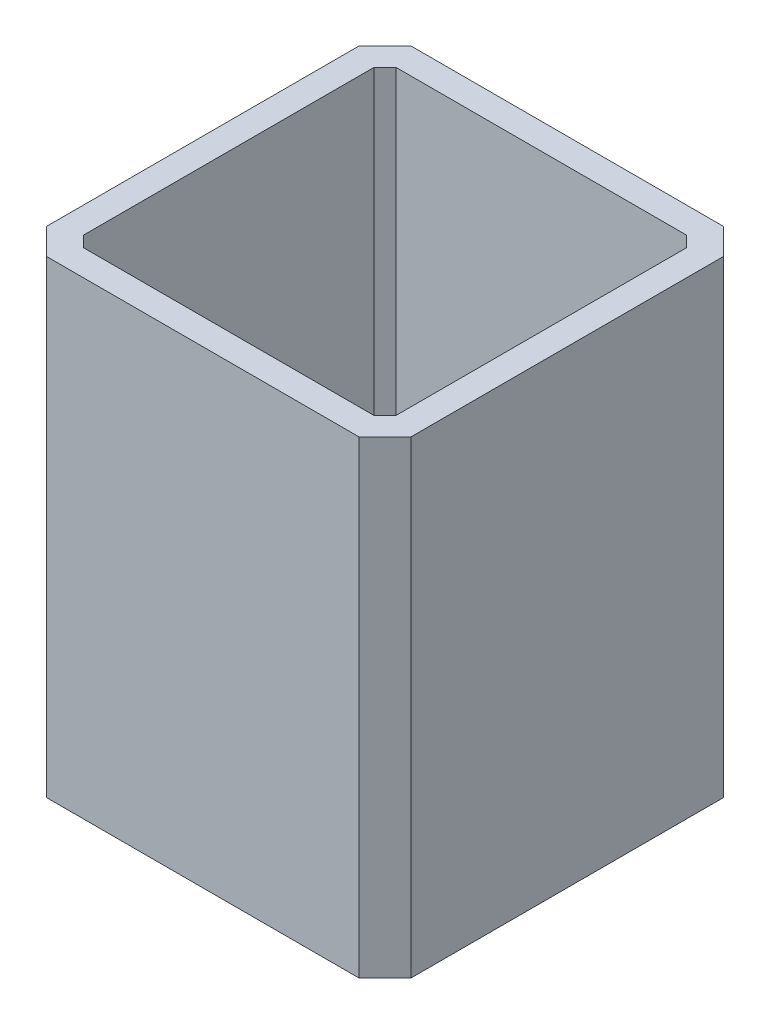
SolidWorks part; units mm, degrees
ref_plane "Front Plane" through (0, 0, 0) normal (0, 0, 1) x (1, 0, 0)
ref_plane "Top Plane" through (0, 0, 0) normal (0, 1, 0) x (1, 0, 0)
ref_plane "Right Plane" through (0, 0, 0) normal (1, 0, 0) x (0, 0, -1)
sketch "Sketch1" plane through (0, 0, 0) normal (0, 1, 0) x (1, 0, 0)
  line L0 (0, 13) -> (1, 14)
  line L1 (1, 0) -> (13, 0)
  line L2 (0, 1) -> (0, 13)
  line L3 (1, 14) -> (13, 14)
  line L4 (14, 1) -> (14, 13)
  line L5 (13, 14) -> (14, 13)
  line L6 (13, 0) -> (14, 1)
  line L7 (1, 0) -> (0, 1)
  point P0 (0, 0)
  point P1 (14, 14)
  point P2 (0, 14)
  point P3 (14, 0)
  dimension "D1" = 14
  dimension "D2" = 14
extrude "Boss-Extrude1" add sketch "Sketch1" along normal blind 18
shell "Shell4" thickness 1
